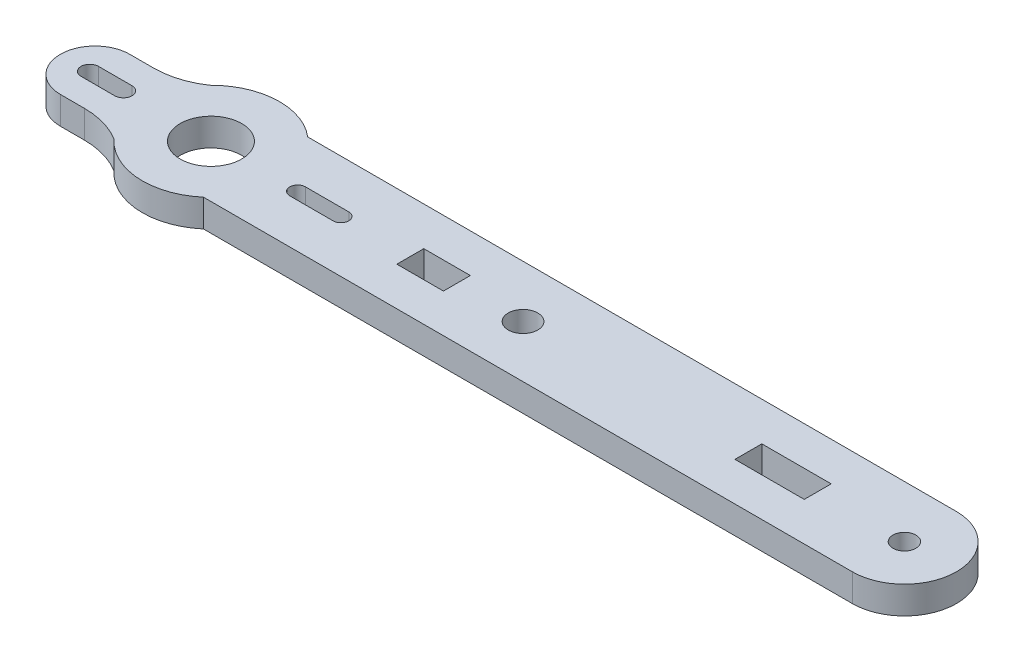
SolidWorks part; units mm, degrees
material "Acrylic (Medium-high impact)"
ref_plane "Front Plane" through (0, 0, 0) normal (0, 0, 1) x (1, 0, 0)
ref_plane "Top Plane" through (0, 0, 0) normal (0, 1, 0) x (1, 0, 0)
ref_plane "Right Plane" through (0, 0, 0) normal (1, 0, 0) x (0, 0, -1)
sketch "Sketch1" plane through (0, 0, 0) normal (0, 1, 0) x (1, 0, 0)
  line L0 (-41.381, -4.957) -> (-41.2088, 5.9181) construction
  line L1 (-30.4202, 6.3945) -> (44.3022, 6.39)
  line L3 (-30.4203, -5.6151) -> (44.3022, -5.6151)
  line L7 (-46.1509, 4.39) -> (-48.9097, 4.39)
  line L8 (-48.9097, -3.6104) -> (-46.1509, -3.6104)
  line L12 (34.32, 1.8852) -> (34.32, 1.9351)
  line L13 (34.32, 1.9351) -> (26.3341, 1.9351)
  line L14 (26.3341, 1.9351) -> (26.3341, 1.8852)
  line L15 (26.3341, 1.8852) -> (26.3341, -1.1149)
  line L16 (26.3341, -1.1149) -> (26.3341, -1.165)
  line L17 (26.3341, -1.165) -> (34.32, -1.165)
  line L18 (34.32, -1.165) -> (34.32, -1.1149)
  line L19 (34.32, -1.1149) -> (34.32, 1.8852)
  line L20 (-7.2331, 1.9349) -> (-12.5968, 1.9349)
  line L21 (-12.5968, 1.9349) -> (-12.5968, -1.1648)
  line L22 (-12.5968, -1.1648) -> (-7.2331, -1.1648)
  line L23 (-7.2331, -1.1648) -> (-7.2331, 1.9349)
  line L24 (-20.5827, -0.5149) -> (-25.5738, -0.5149)
  line L25 (-25.5738, 1.2851) -> (-20.5827, 1.2851)
  line L43 (-49.5122, 1.3852) -> (-45.6381, 1.3852)
  line L44 (-45.6381, -0.6149) -> (-49.5122, -0.6149)
  arc A0 (44.3022, -5.6151) -> (44.3022, 6.39) centre (44.3022, 0.3875) ccw
  circle A1 centre (44.3022, 0.3875) radius 1.3226
  circle A2 centre (0.3831, 0.3852) radius 1.7
  arc A3 (-25.5738, 1.2851) -> (-25.5738, -0.5149) centre (-25.5738, 0.3851) ccw
  arc A4 (-20.5827, 1.2851) -> (-20.5827, -0.5149) centre (-20.5827, 0.3851) cw
  circle A5 centre (-35.5599, 0.3898) radius 3.5436
  arc A6 (-30.4202, 6.3945) -> (-41.2088, 5.9181) centre (-35.5599, 0.3898) ccw
  arc A7 (-49.5122, 1.3852) -> (-49.5122, -0.6149) centre (-49.5122, 0.3852) ccw
  arc A8 (-45.6381, 1.3852) -> (-45.6381, -0.6149) centre (-45.6381, 0.3852) cw
  arc A9 (-48.9097, 4.39) -> (-48.9097, -3.6104) centre (-48.9097, 0.3898) ccw
  arc A10 (-46.1509, -3.6104) -> (-41.381, -4.957) centre (-46.1509, -12.7317) cw
  arc A11 (-46.1509, 4.39) -> (-41.2088, 5.9181) centre (-46.1509, 13.1455) ccw
  arc A12 (-41.381, -4.957) -> (-30.4203, -5.6151) centre (-35.5599, 0.3898) ccw
  point P22 (0.3831, 0.3852)
  point P27 (-35.5599, 0.3898)
  dimension "D1" = 2.6452
  dimension "D2" = 3.4
extrude "Boss-Extrude1" add sketch "Sketch1" along normal blind 3.175
